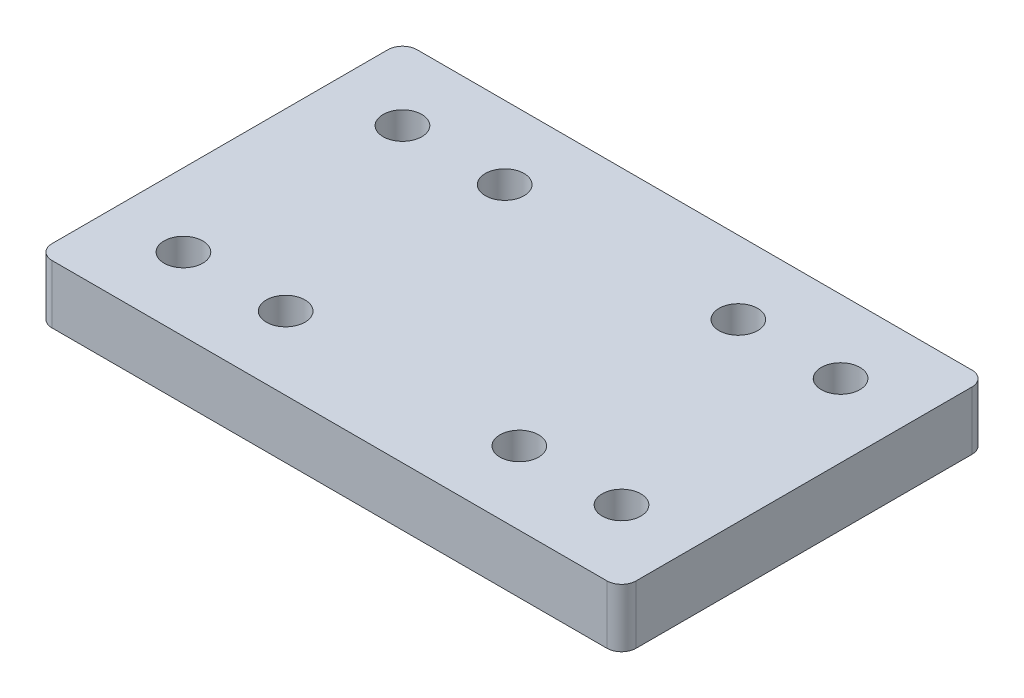
SolidWorks part; units mm, degrees
ref_plane "Front Plane" through (0, 0, 0) normal (0, 0, 1) x (1, 0, 0)
ref_plane "Top Plane" through (0, 0, 0) normal (0, 1, 0) x (1, 0, 0)
ref_plane "Right Plane" through (0, 0, 0) normal (1, 0, 0) x (0, 0, -1)
sketch "Sketch1" plane through (0, 0, 0) normal (0, 1, 0) x (1, 0, 0)
  line L1 (40, -25) -> (-40, -25)
  line L2 (40, -25) -> (40, 25)
  line L3 (40, 25) -> (-40, 25)
  line L4 (-40, -25) -> (-40, 25)
  line L5 (40, -25) -> (-40, 25) construction
  line L6 (40, 25) -> (-40, -25) construction
  line L7 (0, 0) -> (0, 15.7141) construction
  line L8 (0, 0) -> (-17.0023, 0) construction
  point P0 (0, 0)
  dimension "D7" = 80
  dimension "D8" = 50
extrude "Boss-Extrude1" add sketch "Sketch1" along normal blind 8
fillet "Fillet1" radius 2 4 edges at (40, 4, 25) (40, 4, -25) (-40, 4, -25) (-40, 4, 25)
hole_wizard "M5 Clearance Hole1" positions "Sketch3" profile "Sketch2" hole size "M5" standard "ISO"
sketch "Sketch3" plane through (0, 8, 0) normal (0, 1, 0) x (1, 0, 0)
  line L0 (-41.8444, 0) -> (50.1785, 0) construction
  line L1 (-4.4, 0) -> (4.4, 0) construction
  line L3 (0, 26.5493) -> (0, -26.4902) construction
  line L4 (0, -4.4) -> (0, 4.4) construction
  point P0 (-30, 15)
  point P2 (-16, 15)
  point P19 (-16, -15)
  point P20 (-30, -15)
  point P21 (30, -15)
  point P22 (16, -15)
  point P23 (16, 15)
  point P24 (30, 15)
  dimension "D1" = 30
  dimension "D2" = 15
  dimension "D3" = 16
  dimension "D4" = 15
sketch "Sketch2" plane through (-30, 8, -15) normal (1, 0, 0) x (0, 0, 1)
  line L0 (0, 0) -> (0, 9.5923)
  line L1 (0, 9.5923) -> (2.65, 8)
  line L2 (2.65, 8) -> (2.65, 0)
  line L5 (2.65, 0) -> (0, 0)
  line L10 (0, 9.5923) -> (-2.65, 8) construction
  line L11 (0, -6.35) -> (0, 107.95) construction
  dimension "Hole Dia." = 5.3
  dimension "Hole Depth" = 8
  dimension "Drill Angle" = 118
